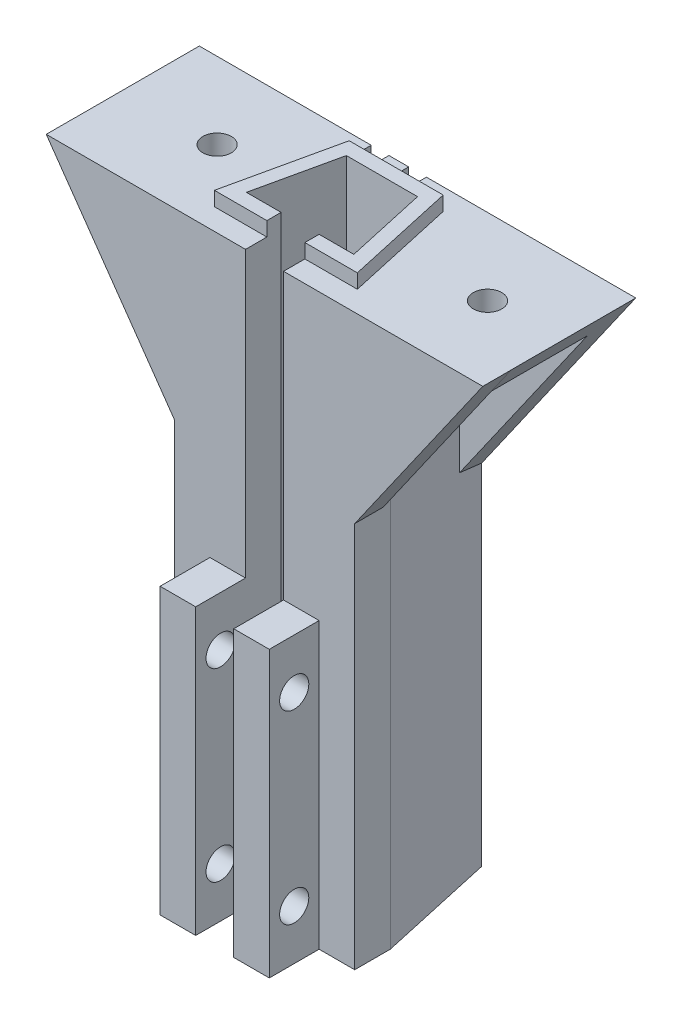
SolidWorks part; units mm, degrees
ref_plane "Front Plane" through (0, 0, 0) normal (0, 0, 1) x (1, 0, 0)
ref_plane "Top Plane" through (0, 0, 0) normal (0, 1, 0) x (1, 0, 0)
ref_plane "Right Plane" through (0, 0, 0) normal (1, 0, 0) x (0, 0, -1)
sketch "Sketch2" plane through (0, 0, 0) normal (0, 1, 0) x (1, 0, 0)
  line L0 (-10.5836, 6.3436) -> (7.4423, 6.3436)
  line L1 (-10.5836, 6.3436) -> (-10.5836, 1.3436)
  line L2 (7.4423, 6.3436) -> (7.4423, 1.3436)
  line L3 (-10.5836, 1.3436) -> (7.4423, 1.3436)
  line L4 (7.4423, 6.3436) -> (11.1002, -10.1564)
  line L5 (7.4423, 6.3436) -> (2.5608, 5.2614)
  line L6 (11.1002, -10.1564) -> (6.2187, -11.2386)
  line L7 (2.5608, 5.2614) -> (6.2187, -11.2386)
  line L8 (-10.5836, 6.3436) -> (-14.2416, -10.1564)
  line L9 (-10.5836, 6.3436) -> (-5.7021, 5.2614)
  line L10 (-14.2416, -10.1564) -> (-9.3601, -11.2386)
  line L11 (-5.7021, 5.2614) -> (-9.3601, -11.2386)
  line L12 (-14.2416, -10.1564) -> (-4.2416, -10.1564)
  line L13 (-14.2416, -10.1564) -> (-14.2416, -15.1564)
  line L14 (-4.2416, -10.1564) -> (-4.2416, -15.1564)
  line L15 (-14.2416, -15.1564) -> (-4.2416, -15.1564)
  line L16 (11.1002, -10.1564) -> (1.1002, -10.1564)
  line L17 (11.1002, -10.1564) -> (11.1002, -15.1564)
  line L18 (1.1002, -10.1564) -> (1.1002, -15.1564)
  line L19 (11.1002, -15.1564) -> (1.1002, -15.1564)
  line L20 (-4.2416, -15.1564) -> (-9.2416, -15.1564)
  line L21 (-4.2416, -15.1564) -> (-4.2416, -22.1564)
  line L22 (-9.2416, -15.1564) -> (-9.2416, -22.1564)
  line L23 (-4.2416, -22.1564) -> (-9.2416, -22.1564)
  line L24 (1.1002, -15.1564) -> (6.1002, -15.1564)
  line L25 (1.1002, -15.1564) -> (1.1002, -22.1564)
  line L26 (6.1002, -15.1564) -> (6.1002, -22.1564)
  line L27 (1.1002, -22.1564) -> (6.1002, -22.1564)
  point P0 (-6.5707, 1.3436)
  point P21 (3.4293, 1.3436)
  point P24 (5.9788, -10.1564)
  point P25 (-9.1202, -10.1564)
  dimension "D1" = 0
  dimension "D2" = 5
  dimension "D3" = 5
  dimension "D4" = 5
  dimension "D5" = 10
  dimension "D6" = 360
  dimension "D7" = 11.5
  dimension "D8" = 5
  dimension "D9" = 5
  dimension "D10" = 11.5
  dimension "D11" = 5
  dimension "D12" = 5
  dimension "D13" = 102.5
  dimension "D14" = 10
  dimension "D15" = 10
  dimension "D16" = 102.5
  dimension "D17" = 15.099
  dimension "D18" = 5.3418
  dimension "D19" = 7
  dimension "D20" = 7
extrude "Boss-Extrude1" add sketch "Sketch2" along normal blind 40 contours L16 L4 L2 L3 L7 | L9 L11 L3 L7 L5 L0 | L8 L12 L11 L3 L1 | L5 L7 L3 L2 | L11 L9 L1 L3 | L13 L15 L14 L12 L11 L10 | L12 L10 L11 | L6 L16 L7 | L19 L17 L6 L7 L16 L18 | L25 L27 L26 L19 | L23 L21 L15 L22
sketch "Sketch3" plane through (-9.2416, 0, 0) normal (-1, 0, 0) x (0, 0, 1)
  line L0 (22.1564, 40) -> (22.1564, 0) construction
  line L1 (15.1564, 40) -> (15.1564, 0) construction
  line L2 (15.1564, 40) -> (22.1564, 40) construction
  line L3 (15.1564, 0) -> (22.1564, 0) construction
  circle A0 centre (18.6564, 33) radius 2.05
  circle A1 centre (18.6564, 7) radius 2.05
  dimension "D5" = 4.1
  dimension "D6" = 4.1
  dimension "D1" = 3.5
  dimension "D2" = 3.5
  dimension "D3" = 3.5
  dimension "D4" = 3.5
  dimension "D7" = 7
  dimension "D8" = 7
extrude "Cut-Extrude2" cut sketch "Sketch3" against normal blind 40
sketch "Sketch4" plane through (0, 40, 0) normal (0, 1, 0) x (1, 0, 0)
  line L0 (-9.1202, -10.1564) -> (-6.5707, 1.3436)
  line L1 (-6.5707, 1.3436) -> (3.4293, 1.3436)
  line L2 (3.4293, 1.3436) -> (5.9788, -10.1564)
  line L3 (5.9788, -10.1564) -> (1.1002, -10.1564)
  line L4 (1.1002, -10.1564) -> (1.1002, -15.1564)
  line L5 (1.1002, -10.1564) -> (1.1002, -22.1564) construction
  line L6 (1.1002, -15.1564) -> (11.1002, -15.1564)
  line L7 (11.1002, -15.1564) -> (11.1002, -10.1564)
  line L8 (11.1002, -10.1564) -> (7.4423, 6.3436)
  line L9 (7.4423, 6.3436) -> (-10.5836, 6.3436)
  line L10 (-10.5836, 6.3436) -> (-14.2416, -10.1564)
  line L11 (-14.2416, -10.1564) -> (-14.2416, -15.1564)
  line L12 (-14.2416, -15.1564) -> (-4.2416, -15.1564)
  line L13 (-4.2416, -10.1564) -> (-4.2416, -22.1564) construction
  line L14 (-4.2416, -15.1564) -> (-4.2416, -10.1564)
  line L33 (-6.5707, 1.3436) -> (3.4293, 1.3436)
  line L34 (3.4293, 1.3436) -> (5.9788, -10.1564)
  line L35 (5.9788, -10.1564) -> (1.1002, -10.1564)
  line L36 (1.1002, -10.1564) -> (1.1002, -22.1564)
  line L37 (1.1002, -22.1564) -> (6.1002, -22.1564)
  line L38 (6.1002, -22.1564) -> (6.1002, -15.1564)
  line L39 (6.1002, -15.1564) -> (11.1002, -15.1564)
  line L40 (11.1002, -15.1564) -> (11.1002, -10.1564)
  line L41 (11.1002, -10.1564) -> (7.4423, 6.3436)
  line L42 (7.4423, 6.3436) -> (-10.5836, 6.3436)
  line L43 (-10.5836, 6.3436) -> (-14.2416, -10.1564)
  line L44 (-14.2416, -10.1564) -> (-14.2416, -15.1564)
  line L45 (-14.2416, -15.1564) -> (-9.2416, -15.1564)
  line L46 (-9.2416, -15.1564) -> (-9.2416, -22.1564)
  line L47 (-9.2416, -22.1564) -> (-4.2416, -22.1564)
  line L48 (-4.2416, -22.1564) -> (-4.2416, -10.1564)
  line L49 (-4.2416, -10.1564) -> (-9.1202, -10.1564)
  line L50 (-9.1202, -10.1564) -> (-6.5707, 1.3436)
  line L51 (-6.5707, 1.3436) -> (3.4293, 1.3436)
  line L52 (3.4293, 1.3436) -> (5.9788, -10.1564)
  line L53 (5.9788, -10.1564) -> (1.1002, -10.1564)
  line L54 (1.1002, -10.1564) -> (1.1002, -22.1564)
  line L55 (1.1002, -22.1564) -> (6.1002, -22.1564)
  line L56 (6.1002, -22.1564) -> (6.1002, -15.1564)
  line L57 (6.1002, -15.1564) -> (11.1002, -15.1564)
  line L58 (11.1002, -15.1564) -> (11.1002, -10.1564)
  line L59 (11.1002, -10.1564) -> (7.4423, 6.3436)
  line L60 (7.4423, 6.3436) -> (-10.5836, 6.3436)
  line L61 (-10.5836, 6.3436) -> (-14.2416, -10.1564)
  line L62 (-14.2416, -10.1564) -> (-14.2416, -15.1564)
  line L63 (-14.2416, -15.1564) -> (-9.2416, -15.1564)
  line L64 (-9.2416, -15.1564) -> (-9.2416, -22.1564)
  line L65 (-9.2416, -22.1564) -> (-4.2416, -22.1564)
  line L66 (-4.2416, -22.1564) -> (-4.2416, -10.1564)
  line L68 (-9.1202, -10.1564) -> (-6.5707, 1.3436)
  line M19 (-6.5707, 1.3436) -> (3.4293, 1.3436)
  line M20 (3.4293, 1.3436) -> (5.9788, -10.1564)
  line M21 (5.9788, -10.1564) -> (1.1002, -10.1564)
  line M22 (1.1002, -10.1564) -> (1.1002, -22.1564)
  line M25 (6.1002, -15.1564) -> (11.1002, -15.1564)
  line M26 (11.1002, -15.1564) -> (11.1002, -10.1564)
  line M27 (11.1002, -10.1564) -> (7.4423, 6.3436)
  line M28 (7.4423, 6.3436) -> (-10.5836, 6.3436)
  line M29 (-10.5836, 6.3436) -> (-14.2416, -10.1564)
  line M30 (-14.2416, -10.1564) -> (-14.2416, -15.1564)
  line M31 (-14.2416, -15.1564) -> (-9.2416, -15.1564)
  line M34 (-4.2416, -22.1564) -> (-4.2416, -10.1564)
  line M35 (-4.2416, -10.1564) -> (-9.1202, -10.1564)
  line M36 (-9.1202, -10.1564) -> (-6.5707, 1.3436)
  dimension "D1" = 0
extrude "Boss-Extrude2" add sketch "Sketch4" along normal blind 40 contours L12 L6 M31 M34 M35 M36 M19 M20 M21 M22 M25 M26 M27 M28 M29 M30
sketch "Sketch7" plane through (0, 0, -6.3436) normal (0, 0, -1) x (-1, 0, 0)
  line L0 (-7.4423, 80) -> (-7.4423, 0) construction
  line L1 (3.8177, 3.2) -> (-0.6823, 3.2)
  line L2 (3.8177, 3.2) -> (3.8177, 5.2)
  line L3 (3.8177, 5.2) -> (-0.6823, 5.2)
  line L4 (-0.6823, 3.2) -> (-0.6823, 5.2)
  line L5 (10.5836, 80) -> (10.5836, 0) construction
  line L6 (10.5836, 0) -> (-7.4423, 0) construction
  point P4 (-0.6823, 4.2)
  dimension "D1" = 6.76
  dimension "D2" = 4.5
  dimension "D3" = 2
  dimension "D4" = 6.7658
  dimension "D5" = 3.2
extrude "Cut-Extrude3" cut sketch "Sketch7" against normal through all
sketch "Sketch8" plane through (0, 0, 10.1564) normal (0, 0, -1) x (-1, 0, 0)
  line L0 (4.2416, 80) -> (4.2416, 0) construction
  line L1 (5.2416, 5.2) -> (4.2416, 5.2)
  line L2 (5.2416, 5.2) -> (5.2416, 3.2)
  line L3 (5.2416, 3.2) -> (4.2416, 3.2)
  line L4 (4.2416, 5.2) -> (4.2416, 3.2)
  line L5 (9.1202, 0) -> (4.2416, 0) construction
  dimension "D1" = 2
  dimension "D2" = 1
  dimension "D3" = 3.2
extrude "Cut-Extrude4" cut sketch "Sketch8" against normal blind 5
sketch "Sketch9" plane through (0, 80, 0) normal (0, 1, 0) x (1, 0, 0)
  line L0 (1.1002, -10.1564) -> (1.1002, -12.1564)
  line L1 (1.1002, -10.1564) -> (1.1002, -15.1564) construction
  line L2 (1.1002, -10.1564) -> (5.9788, -10.1564)
  line L3 (5.9788, -10.1564) -> (3.4293, 1.3436)
  line L4 (3.4293, 1.3436) -> (-6.5707, 1.3436)
  line L5 (-6.5707, 1.3436) -> (-9.1202, -10.1564)
  line L6 (-9.1202, -10.1564) -> (-4.2416, -10.1564)
  line L7 (-4.2416, -10.1564) -> (-4.2416, -12.1564)
  line L8 (-4.2416, -15.1564) -> (-4.2416, -10.1564) construction
  line L9 (-4.2416, -12.1564) -> (-11.6121, -12.1564)
  line L10 (-11.6121, -12.1564) -> (-8.1758, 3.3436)
  line L11 (-8.1758, 3.3436) -> (5.0345, 3.3436)
  line L12 (5.0345, 3.3436) -> (8.4708, -12.1564)
  line L13 (8.4708, -12.1564) -> (1.1002, -12.1564)
  dimension "D1" = 2
  dimension "D2" = 2
  dimension "D3" = 2
  dimension "D4" = 2
  dimension "D5" = 2
  dimension "D6" = 13.2103
extrude "Boss-Extrude3" add sketch "Sketch9" along normal blind 2
sketch "Sketch10" plane through (-5.2416, 0, 0) normal (1, 0, 0) x (0, 0, -1)
  line L0 (-15.1564, 5.2) -> (-10.1564, 5.2) construction
  line L1 (-15.1564, 3.2) -> (-12.6564, 3.2)
  line L2 (-15.1564, 3.2) -> (-15.1564, 5.2)
  line L3 (-15.1564, 5.2) -> (-12.6564, 5.2)
  line L4 (-12.6564, 3.2) -> (-12.6564, 5.2)
  dimension "D1" = 2.5
extrude "Cut-Extrude5" cut sketch "Sketch10" against normal blind 11
sketch "Sketch11" plane through (0, 0, 15.1564) normal (0, 0, 1) x (1, 0, 0)
  line L0 (11.1002, 54.2933) -> (29.1002, 80)
  line L1 (11.1002, 80) -> (11.1002, 0) construction
  line L2 (29.1002, 80) -> (11.1002, 80)
  line L3 (11.1002, 80) -> (11.1002, 54.2933)
  line L4 (-14.2416, 54.2933) -> (-32.2416, 80)
  line L5 (-14.2416, 80) -> (-14.2416, 5.2) construction
  line L6 (-32.2416, 80) -> (-14.2416, 80)
  line L7 (-14.2416, 80) -> (-14.2416, 54.2933)
  dimension "D1" = 18
  dimension "D2" = 18
  dimension "D3" = 55
  dimension "D4" = 55
extrude "Boss-Extrude4" add sketch "Sketch11" against normal blind 4
sketch "Sketch15" plane through (0, 0, -6.3436) normal (0, 0, -1) x (-1, 0, 0)
  line L0 (-7.4423, 80) -> (-7.4423, 49.0806)
  line L1 (-7.4423, 80) -> (-7.4423, 0) construction
  line L2 (-7.4423, 49.0806) -> (-29.0923, 80)
  line L3 (-29.0923, 80) -> (-7.4423, 80)
  line L4 (10.5836, 80) -> (10.5836, 49.0806)
  line L5 (10.5836, 80) -> (10.5836, 0) construction
  line L6 (10.5836, 49.0806) -> (32.2336, 80)
  line L7 (32.2336, 80) -> (10.5836, 80)
  dimension "D1" = 55
  dimension "D2" = 21.65
  dimension "D3" = 55
  dimension "D4" = 21.65
extrude "Boss-Extrude7" add sketch "Sketch15" against normal blind 4
sketch "Sketch16" plane through (0, 0, -6.3436) normal (0, 0, -1) x (-1, 0, 0)
  line L0 (32.2336, 80) -> (29.4328, 76)
  line L1 (10.5836, 49.0806) -> (32.2336, 80) construction
  line L2 (29.4328, 76) -> (10.2336, 76)
  line L3 (10.2336, 76) -> (10.2336, 80)
  line L4 (-29.0923, 80) -> (32.2336, 80) construction
  line L5 (10.2336, 80) -> (32.2336, 80)
  line L6 (-29.0923, 80) -> (-26.2914, 76)
  line L7 (-29.0923, 80) -> (-7.4423, 49.0806) construction
  line L8 (-26.2914, 76) -> (-7.0923, 76)
  line L9 (-7.0923, 76) -> (-7.0923, 80)
  line L10 (-7.0923, 80) -> (-29.0923, 80)
  dimension "D1" = 22
  dimension "D2" = 22
  dimension "D3" = 4
  dimension "D4" = 4
extrude "Boss-Extrude8" add sketch "Sketch16" against normal blind 19
sketch "Sketch17" plane through (0, 76, 0) normal (0, -1, 0) x (-1, 0, 0)
  line L0 (11.4704, 2.3436) -> (29.4328, 2.3436) construction
  line L1 (29.4328, -11.1564) -> (14.2416, -11.1564) construction
  line L2 (-26.2914, -11.1564) -> (-11.1002, -11.1564) construction
  line L3 (-26.2914, -11.1564) -> (-26.2914, 2.3436) construction
  line L4 (29.4328, -11.1564) -> (29.4328, 2.3436) construction
  circle A0 centre (-19.0195, -4.4064) radius 2
  circle A1 centre (18.9805, -4.4064) radius 2
  dimension "D1" = 4
  dimension "D2" = 4
  dimension "D3" = 6.75
  dimension "D4" = 6.75
  dimension "D5" = 6.75
  dimension "D6" = 7.272
  dimension "D7" = 10.4522
extrude "Cut-Extrude7" cut sketch "Sketch17" against normal blind 19
sketch "Sketch18" plane through (0, 0, 12.6564) normal (0, 0, 1) x (1, 0, 0)
  line L0 (-14.2416, 3.2) -> (-5.2416, 3.2) construction
  line L1 (-14.2416, 5.2) -> (-11.7416, 5.2)
  line L2 (-14.2416, 5.2) -> (-14.2416, 3.2)
  line L3 (-14.2416, 3.2) -> (-11.7416, 3.2)
  line L4 (-11.7416, 5.2) -> (-11.7416, 3.2)
  dimension "D1" = 2.5
extrude "Cut-Extrude8" cut sketch "Sketch18" against normal blind 2.5
sketch "Sketch19" plane through (0, 0, 10.1564) normal (0, 0, 1) x (1, 0, 0)
  line L0 (-14.2416, 3.2) -> (-11.7416, 3.2) construction
  line L1 (-14.2416, 5.2) -> (-11.7416, 5.2)
  line L2 (-14.2416, 5.2) -> (-14.2416, 3.2)
  line L3 (-14.2416, 3.2) -> (-11.7416, 3.2)
  line L4 (-11.7416, 5.2) -> (-11.7416, 3.2)
  line L5 (-11.7416, 3.2) -> (-11.7416, 5.2) construction
extrude "Cut-Extrude9" cut sketch "Sketch19" along direction (-0.2164, 0, 0.9763) on the side against the normal blind 19.5
sketch "Sketch20" plane through (-9.0454, 0, -2.0053) normal (-0.9763, 0, -0.2164) x (-0.2164, 0, 0.9763)
  line L0 (-4.4436, 3.2) -> (12.457, 3.2) construction
  line L1 (-4.4436, 5.2) -> (-2.1436, 5.2)
  line L2 (-4.4436, 5.2) -> (-4.4436, 3.2)
  line L3 (-4.4436, 3.2) -> (-2.1436, 3.2)
  line L4 (-2.1436, 5.2) -> (-2.1436, 3.2)
  dimension "D1" = 2.3
extrude "Cut-Extrude10" cut sketch "Sketch20" along direction (1, 0, 0) on the side against the normal blind 2.5
sketch "Sketch21" plane through (0, 0, -6.3436) normal (0, 0, -1) x (-1, 0, 0)
  line L0 (3.8177, 5.2) -> (-0.6823, 5.2) construction
  line L1 (2.8177, 5.2) -> (0.3177, 5.2)
  line L2 (2.8177, 5.2) -> (2.8177, 80)
  line L3 (2.8177, 80) -> (0.3177, 80)
  line L4 (0.3177, 5.2) -> (0.3177, 80)
  line L5 (-29.0923, 80) -> (32.2336, 80) construction
  line L7 (5.5836, 5.2) -> (8.0836, 5.2)
  line L8 (5.5836, 5.2) -> (5.5836, 80)
  line L9 (5.5836, 80) -> (8.0836, 80)
  line L10 (8.0836, 5.2) -> (8.0836, 80)
  dimension "D1" = 2.5
  dimension "D2" = 2.5
  dimension "D3" = 1
  dimension "D4" = 1
extrude "Cut-Extrude11" cut sketch "Sketch21" against normal blind 2.5
